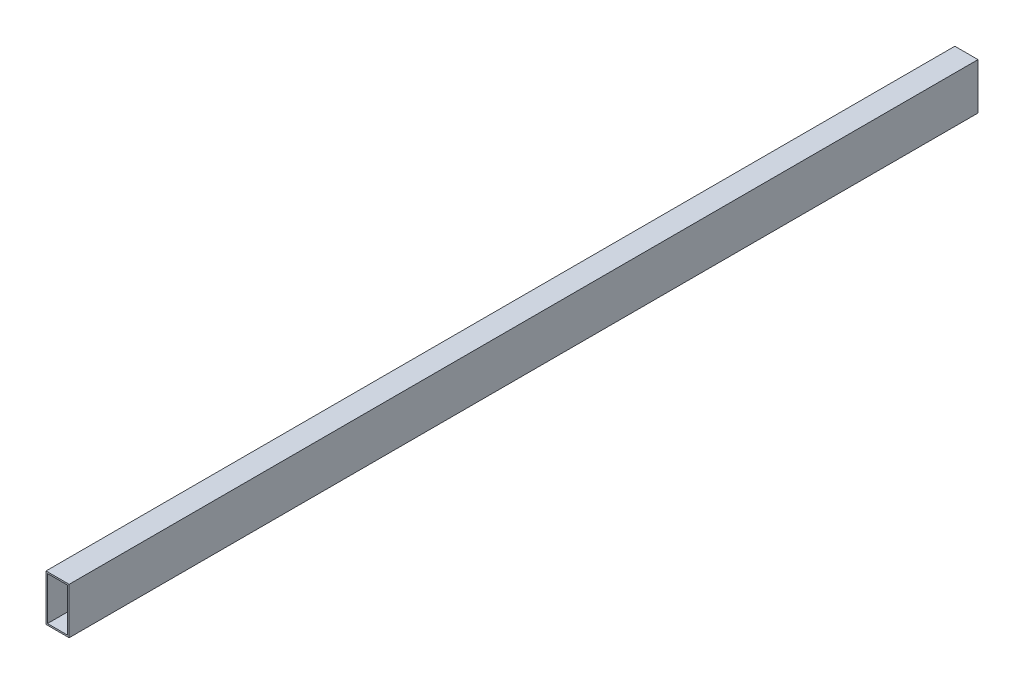
SolidWorks part; units mm, degrees
material "6061 Alloy"
ref_plane "Front Plane" through (0, 0, 0) normal (0, 0, 1) x (1, 0, 0)
ref_plane "Top Plane" through (0, 0, 0) normal (0, 1, 0) x (1, 0, 0)
ref_plane "Right Plane" through (0, 0, 0) normal (1, 0, 0) x (0, 0, -1)
sketch "Sketch1" plane through (0, 0, 0) normal (0, 0, 1) x (1, 0, 0)
  line L1 (-48.4372, -30.1994) -> (-23.0372, -30.1994)
  line L2 (-48.4372, -30.1994) -> (-48.4372, 20.6006)
  line L3 (-48.4372, 20.6006) -> (-23.0372, 20.6006)
  line L4 (-23.0372, -30.1994) -> (-23.0372, 20.6006)
  dimension "D1" = 25.4
  dimension "D2" = 50.8
extrude "Boss-Extrude1" add sketch "Sketch1" along normal blind 996.95
sketch "Sketch2" plane through (0, 0, 996.95) normal (0, 0, 1) x (1, 0, 0)
  line L0 (-48.4372, 20.6006) -> (-48.4372, -30.1994) construction
  line L1 (-46.7862, 18.9496) -> (-24.6882, 18.9496)
  line L2 (-46.7862, 18.9496) -> (-46.7862, -28.5484)
  line L3 (-46.7862, -28.5484) -> (-24.6882, -28.5484)
  line L4 (-24.6882, 18.9496) -> (-24.6882, -28.5484)
  line L5 (-46.7862, 18.9496) -> (-24.6882, -28.5484) construction
  line L6 (-46.7862, -28.5484) -> (-24.6882, 18.9496) construction
  line L7 (-23.0372, -30.1994) -> (-23.0372, 20.6006) construction
  line L8 (-23.0372, 20.6006) -> (-48.4372, 20.6006) construction
  line L9 (-48.4372, -30.1994) -> (-23.0372, -30.1994) construction
  point P0 (-35.7372, -4.7994)
  dimension "D1" = 1.651
  dimension "D2" = 1.651
  dimension "D3" = 1.651
  dimension "D4" = 1.651
extrude "Cut-Extrude1" cut sketch "Sketch2" against normal through all
